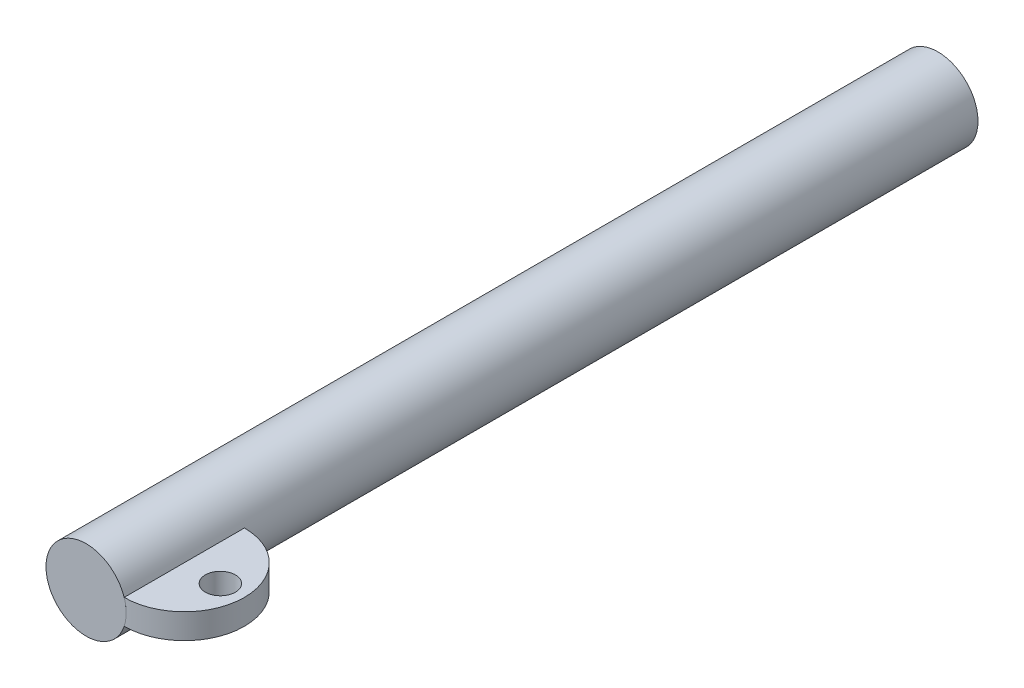
SolidWorks part; units mm, degrees
ref_plane "Front" through (0, 0, 0) normal (0, 0, 1) x (1, 0, 0)
ref_plane "Top" through (0, 0, 0) normal (0, 1, 0) x (1, 0, 0)
ref_plane "Right" through (0, 0, 0) normal (1, 0, 0) x (0, 0, -1)
sketch "Sketch1" plane through (0, 0, 0) normal (0, 0, 1) x (1, 0, 0)
  circle A0 centre (0, 0) radius 20
  point P3 (-20, 0)
  dimension "D1" = 40
extrude "Base-Extrude" add sketch "Sketch1" against normal blind 425
ref_plane "Plane2" through (0, 0, 0) normal (0, 1, 0) x (-1, 0, 0)
sketch "Sketch4" plane through (0, 0, 0) normal (0, 1, 0) x (-1, 0, 0)
  line L0 (-19, -60) -> (-19, 0)
  arc A0 (-19, 0) -> (-19, -60) centre (-19, -30) ccw
  circle A1 centre (-37, -30) radius 7.5
  dimension "D1" = 18
  dimension "D2" = 15
  dimension "D4" = 30
  dimension "D3" = 19
  dimension "D5" = 0
  dimension "D6" = 30
extrude "Boss-Extrude1" add sketch "Sketch4" along normal mid plane 12.5
sketch "Sketch5" plane through (0, 0, -425) normal (0, 0, -1) x (-1, 0, 0)
  circle A0 centre (0, 0) radius 20
